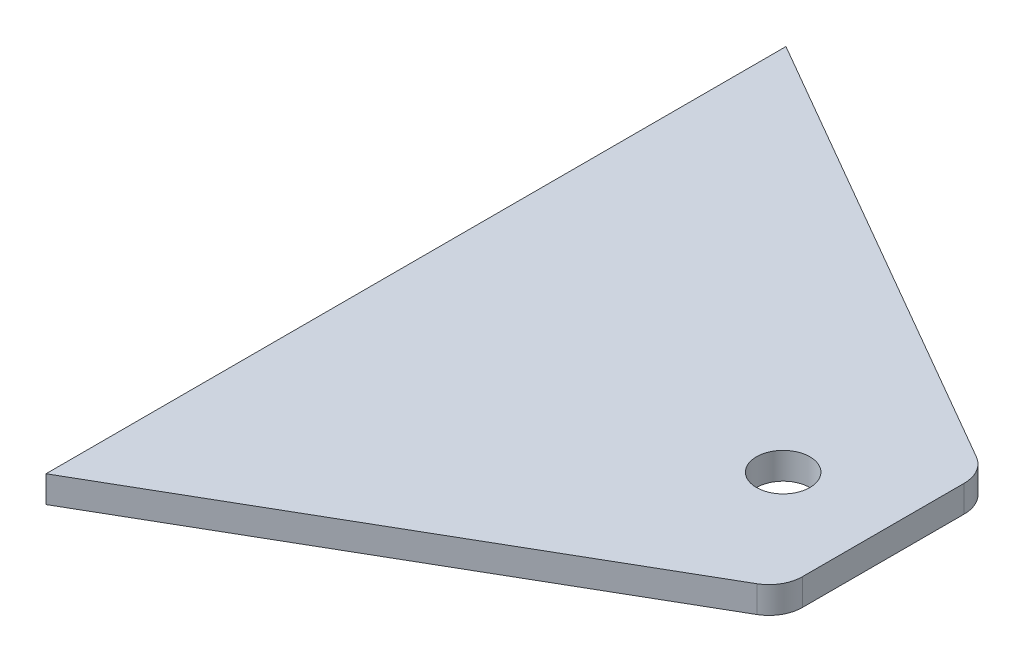
SolidWorks part; units mm, degrees
ref_plane "Front Plane" through (0, 0, 0) normal (0, 0, 1) x (1, 0, 0)
ref_plane "Top Plane" through (0, 0, 0) normal (0, 1, 0) x (1, 0, 0)
ref_plane "Right Plane" through (0, 0, 0) normal (1, 0, 0) x (0, 0, -1)
sketch "Sketch2" plane through (0, 0, 0) normal (0, 1, 0) x (1, 0, 0)
  line L4 (70, -37.726) -> (70, -7.726)
  line L5 (70, -37.726) -> (0, -78.1405)
  line L7 (0, 32.6885) -> (70, -7.726)
  line L8 (0, -78.1405) -> (0, 32.6885)
  point P7 (70, -7.726)
  point P10 (70, -37.726)
  dimension "D3" = 60
  dimension "D4" = 60
  dimension "D1" = 70
  dimension "D2" = 30
extrude "Boss-Extrude1" add sketch "Sketch2" along normal blind 4
sketch "Sketch3" plane through (0, 4, 0) normal (0, 1, 0) x (1, 0, 0)
  line L0 (70, -37.726) -> (70, -7.726) construction
  circle A0 centre (55, -22.726) radius 4
  dimension "D1" = 8
  dimension "D2" = 15
  dimension "D3" = 15
extrude "Cut-Extrude1" cut sketch "Sketch3" against normal through all
fillet "Fillet1" radius 5 2 edges at (70, 2, 37.726) (70, 2, 7.726)
